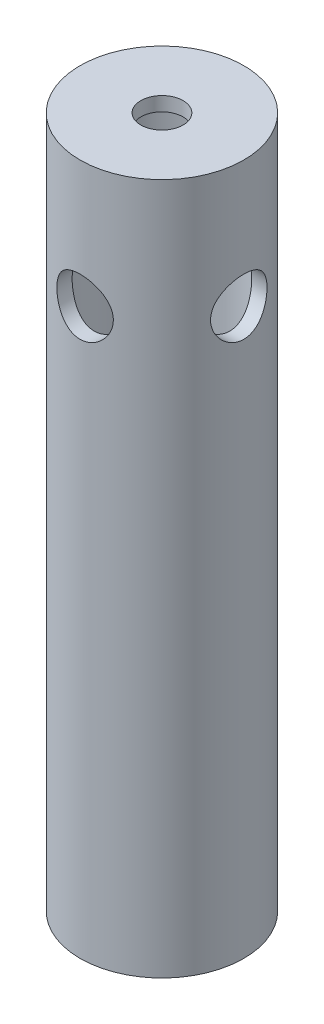
SolidWorks part; units mm, degrees
material "Copper"
ref_plane "Front Plane" through (0, 0, 0) normal (0, 0, 1) x (1, 0, 0)
ref_plane "Top Plane" through (0, 0, 0) normal (0, 1, 0) x (1, 0, 0)
ref_plane "Right Plane" through (0, 0, 0) normal (1, 0, 0) x (0, 0, -1)
sketch "Sketch1" plane through (0, 0, 0) normal (0, 1, 0) x (1, 0, 0)
  circle A0 centre (0, 0) radius 5.8
  dimension "D1" = 11.6
extrude "Boss-Extrude1" add sketch "Sketch1" along normal blind 49
shell "Shell2" thickness 1
sketch "Sketch5" plane through (0, 0, 0) normal (0, 0, 1) x (1, 0, 0)
  circle A0 centre (0, 40) radius 2
  dimension "D1" = 4
  dimension "D2" = 40
extrude "Cut-Extrude1" cut sketch "Sketch5" against normal through all both and the other way through all
pattern_circular "CirPattern1" count 2 over 90 about axis through (0, 49, 0) along (0, -1, 0) of "Cut-Extrude1"
sketch "Sketch6" plane through (0, 49, 0) normal (0, 1, 0) x (1, 0, 0)
  circle A0 centre (0, 0) radius 1.5
  dimension "D1" = 3
extrude "Cut-Extrude2" cut sketch "Sketch6" against normal up to next
